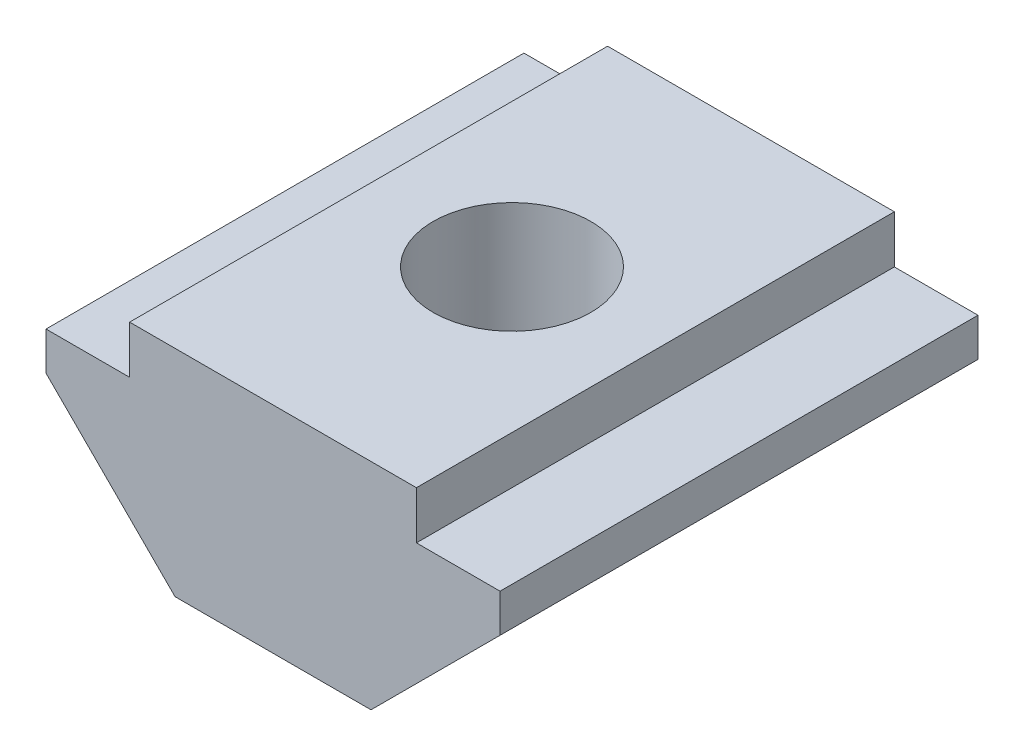
SolidWorks part; units mm, degrees
ref_plane "前视基准面" through (0, 0, 0) normal (0, 0, 1) x (1, 0, 0)
ref_plane "上视基准面" through (0, 0, 0) normal (0, 1, 0) x (1, 0, 0)
ref_plane "右视基准面" through (0, 0, 0) normal (1, 0, 0) x (0, 0, -1)
sketch "草图1" plane through (0, 0, 0) normal (0, 0, 1) x (1, 0, 0)
  line L0 (-4.75, 1.886) -> (2.05, -0.814) construction
  line L5 (2.05, -0.814) -> (-2.05, -0.814)
  line L6 (-2.05, -0.814) -> (-4.75, 1.886)
  line L11 (4.75, 1.886) -> (-2.05, -0.814) construction
  line L12 (-4.75, 1.886) -> (4.75, 1.886)
  line L13 (2.05, -0.814) -> (4.75, 1.886)
  line L19 (-4.75, 1.886) -> (4.75, 1.886)
  line L20 (-4.75, 1.886) -> (-4.75, 2.686)
  line L21 (-4.75, 2.686) -> (4.75, 2.686)
  line L22 (4.75, 1.886) -> (4.75, 2.686)
  line L23 (-3, 3.686) -> (3, 3.686)
  line L24 (-3, 3.686) -> (-3, 2.686)
  line L25 (-3, 2.686) -> (3, 2.686)
  line L26 (3, 3.686) -> (3, 2.686)
  line L27 (-3, 3.686) -> (3, 2.686) construction
  line L28 (-3, 2.686) -> (3, 3.686) construction
  point P4 (0, 0)
  point P5 (0, 3.186)
  dimension "D1" = 0.8
  dimension "E" = 4.5
  dimension "B" = 9.5
  dimension "D4" = 90
  dimension "A" = 6
  dimension "T" = 3.5
extrude "凸台-拉伸1" add sketch "草图1" along normal mid plane 10
hole_wizard " 螺纹孔0" positions "草图2" profile "草图3" tap size "M4" standard "GB" end condition through all
sketch "草图2" plane through (0, 3.686, 0) normal (0, 1, 0) x (1, 0, 0)
  point P0 (0, 0)
cosmetic thread "孔螺蚊线1" parameters "D2"=4
sketch "草图3" plane through (0, 3.686, 0) normal (1, 0, 0) x (0, 0, 1)
  line L0 (0, 0) -> (0, 4.5)
  line L1 (0, 4.5) -> (1.65, 4.5)
  line L2 (1.65, 4.5) -> (1.65, 0)
  line L5 (1.65, 0) -> (0, 0)
  line L11 (0, -6.35) -> (0, 107.95) construction
  dimension "通孔螺纹孔钻头直径" = 3.3
  dimension "通孔螺纹孔钻头深度" = 4.5
